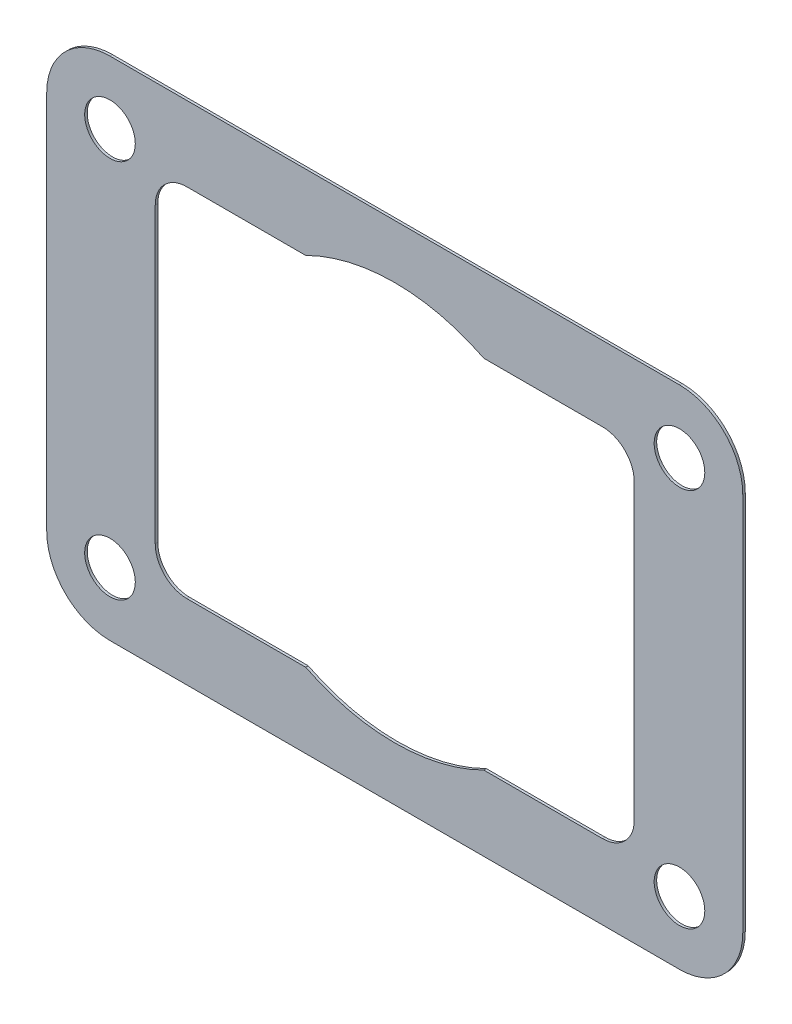
SolidWorks part; units mm, degrees
material "VITON"
ref_plane "Front" through (0, 0, 0) normal (0, 0, 1) x (1, 0, 0)
ref_plane "Top" through (0, 0, 0) normal (0, 1, 0) x (1, 0, 0)
ref_plane "Right" through (0, 0, 0) normal (1, 0, 0) x (0, 0, -1)
sketch "Sketch1" plane through (0, 0, 0) normal (0, 0, 1) x (1, 0, 0)
  line L0 (17.8767, 35.7886) -> (41.7195, 35.7886)
  line L1 (-57.15, -50.8) -> (57.15, -50.8)
  line L2 (-69.85, -38.1) -> (-69.85, 38.1)
  line L3 (-57.15, 50.8) -> (57.15, 50.8)
  line L4 (69.85, -38.1) -> (69.85, 38.1)
  line L5 (-69.85, -50.8) -> (69.85, 50.8) construction
  line L6 (-69.85, 50.8) -> (69.85, -50.8) construction
  line L7 (-41.7195, -35.7886) -> (-17.8767, -35.7886)
  line L8 (-48.0695, -29.4386) -> (-48.0695, 29.4386)
  line L9 (-41.7195, 35.7886) -> (-17.8767, 35.7886)
  line L10 (48.0695, -29.4386) -> (48.0695, 29.4386)
  line L11 (-48.0695, -35.7886) -> (48.0695, 35.7886) construction
  line L12 (-48.0695, 35.7886) -> (48.0695, -35.7886) construction
  line L13 (17.8767, -35.7886) -> (41.7195, -35.7886)
  arc A0 (-57.15, -50.8) -> (-69.85, -38.1) centre (-57.15, -38.1) cw
  arc A1 (57.15, -50.8) -> (69.85, -38.1) centre (57.15, -38.1) ccw
  arc A2 (57.15, 50.8) -> (69.85, 38.1) centre (57.15, 38.1) cw
  arc A3 (-69.85, 38.1) -> (-57.15, 50.8) centre (-57.15, 38.1) cw
  circle A4 centre (-57.15, 38.1) radius 5.08
  circle A5 centre (-57.15, -38.1) radius 5.08
  circle A6 centre (57.15, -38.1) radius 5.08
  circle A7 centre (57.15, 38.1) radius 5.08
  arc A8 (41.7195, 35.7886) -> (48.0695, 29.4386) centre (41.7195, 29.4386) cw
  arc A9 (41.7195, -35.7886) -> (48.0695, -29.4386) centre (41.7195, -29.4386) ccw
  arc A10 (-41.7195, -35.7886) -> (-48.0695, -29.4386) centre (-41.7195, -29.4386) cw
  arc A11 (-48.0695, 29.4386) -> (-41.7195, 35.7886) centre (-41.7195, 29.4386) cw
  arc A13 (17.8767, 35.7886) -> (-17.8767, 35.7886) centre (0, 0) ccw
  arc A16 (-17.8767, -35.7886) -> (17.8767, -35.7886) centre (0, 0) ccw
  point P0 (0, 0)
  point P22 (0, 0)
  dimension "D3" = 12.7
  dimension "D4" = 10.16
  dimension "D7" = 6.35
  dimension "D8" = 80.01
  dimension "D1" = 139.7
  dimension "D2" = 101.6
  dimension "D5" = 96.139
  dimension "D6" = 71.5772
extrude "Boss-Extrude1" add sketch "Sketch1" along normal blind 0.508
